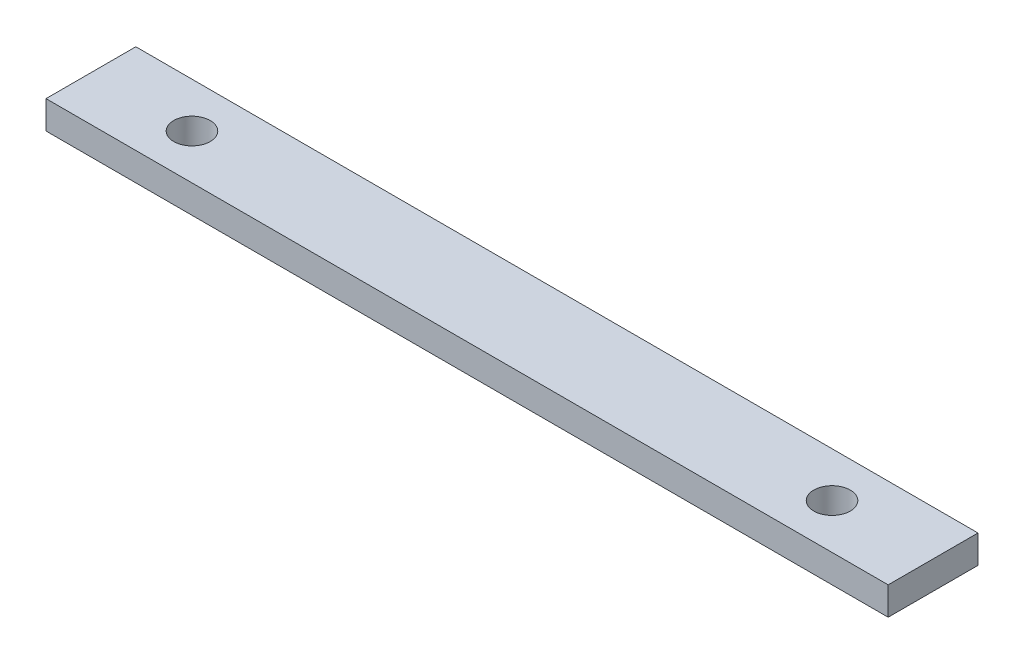
SolidWorks part; units mm, degrees
ref_plane "Front Plane" through (0, 0, 0) normal (0, 0, 1) x (1, 0, 0)
ref_plane "Top Plane" through (0, 0, 0) normal (0, 1, 0) x (1, 0, 0)
ref_plane "Right Plane" through (0, 0, 0) normal (1, 0, 0) x (0, 0, -1)
sketch "Sketch1" plane through (0, 0, 0) normal (0, 1, 0) x (1, 0, 0)
  line L0 (-75, -8) -> (75, 8) construction
  line L1 (-75, -8) -> (75, -8)
  line L2 (-75, -8) -> (-75, 8)
  line L3 (-75, 8) -> (75, 8)
  line L4 (75, -8) -> (75, 8)
  point P4 (0, 0)
  dimension "D1" = 16
  dimension "D2" = 150
extrude "Boss-Extrude1" add sketch "Sketch1" along normal blind 5
sketch "Sketch2" plane through (0, 5, 0) normal (0, 1, 0) x (1, 0, 0)
  line L0 (-75, 0) -> (-57, 0) construction
  line L1 (-75, 8) -> (-75, -8) construction
  line L2 (0, 0) -> (0, 29.0079) construction
  circle A0 centre (-57, 0) radius 3.25
  circle A1 centre (57, 0) radius 3.25
  dimension "D1" = 6.5
  dimension "D2" = 14.75
extrude "Cut-Extrude1" cut sketch "Sketch2" against normal up to next
